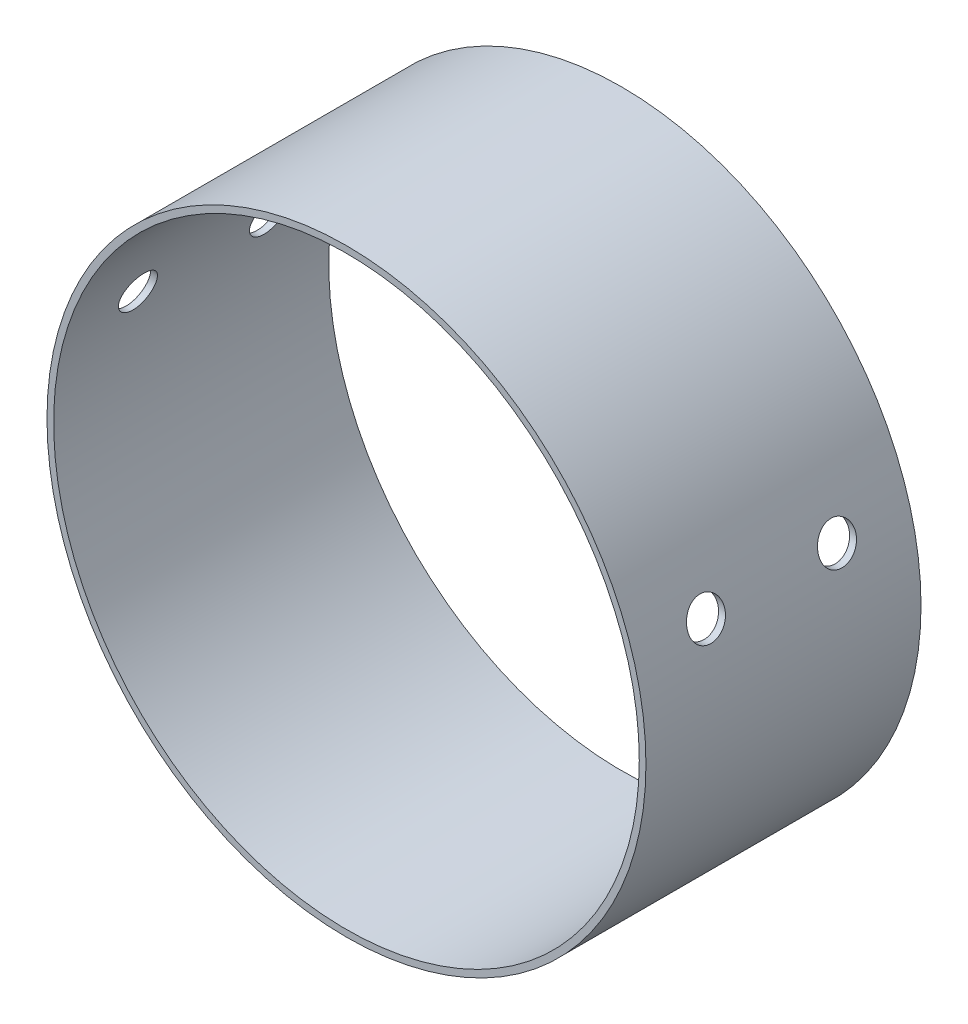
SolidWorks part; units mm, degrees
material "E-Glass Fiber"
ref_plane "Front Plane" through (0, 0, 0) normal (0, 0, 1) x (1, 0, 0)
ref_plane "Top Plane" through (0, 0, 0) normal (0, 1, 0) x (1, 0, 0)
ref_plane "Right Plane" through (0, 0, 0) normal (1, 0, 0) x (0, 0, -1)
sketch "Sketch1" plane through (0, 0, 0) normal (0, 0, 1) x (1, 0, 0)
  circle A0 centre (0, 0) radius 50.8
  circle A1 centre (0, 0) radius 49.6697
  dimension "D1" = 101.6
  dimension "D2" = 99.3394
extrude "Boss-Extrude1" add sketch "Sketch1" along normal mid plane 46.6598
sketch "Sketch2" plane through (0, 0, 0) normal (1, 0, 0) x (0, 0, -1)
  line L0 (0, 0) -> (0, 14.2037) construction
  line L1 (0, 14.2037) -> (11.1125, 14.2037) construction
  line L2 (0, 14.2037) -> (-11.1125, 14.2037) construction
  line L4 (0, 55.88) -> (0, -55.88) construction
  circle A0 centre (-11.1125, 14.2037) radius 3.175
  circle A1 centre (11.1125, 14.2037) radius 3.175
  dimension "D3" = 6.35
  dimension "D1" = 14.2037
  dimension "D2" = 22.225
extrude "Cut-Extrude1" cut sketch "Sketch2" against normal through all and the other way through all
